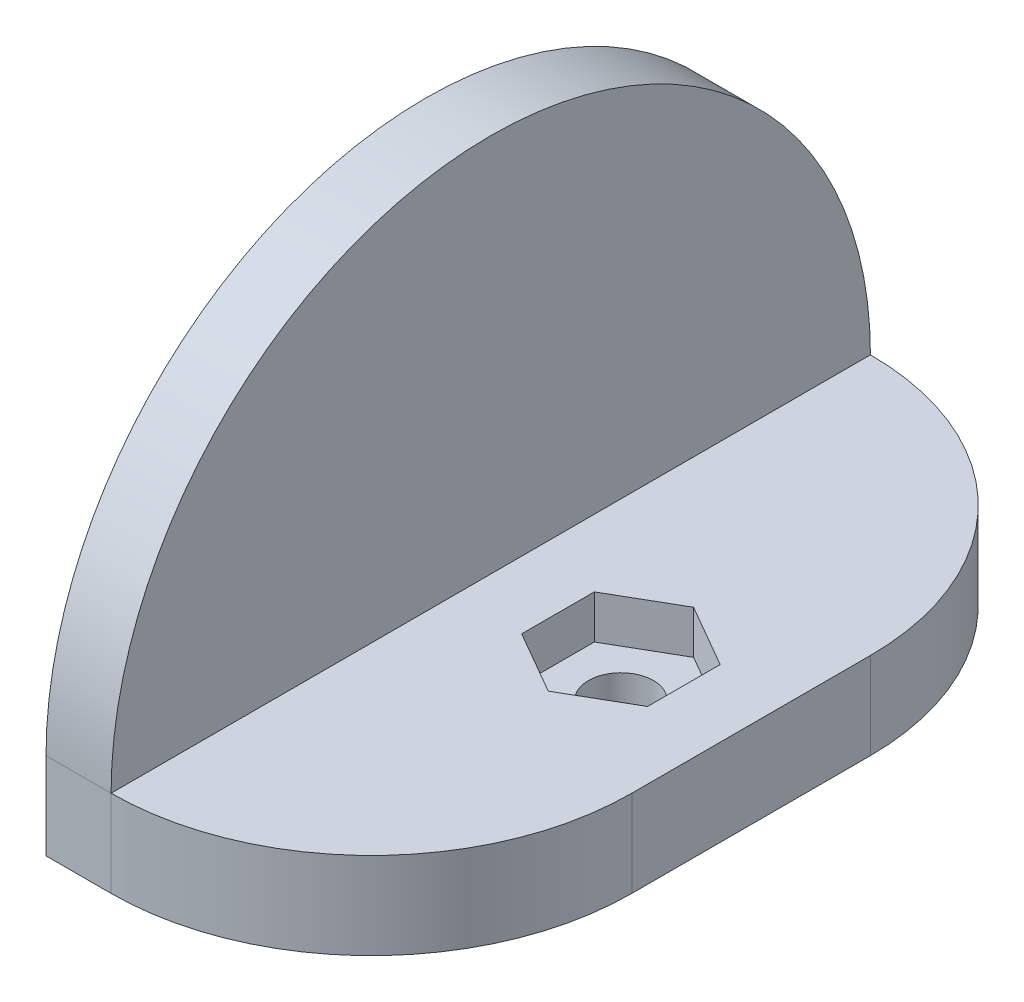
SolidWorks part; units mm, degrees
ref_plane "Alzado" through (0, 0, 0) normal (0, 0, 1) x (1, 0, 0)
ref_plane "Planta" through (0, 0, 0) normal (0, 1, 0) x (1, 0, 0)
ref_plane "Vista lateral" through (0, 0, 0) normal (1, 0, 0) x (0, 0, -1)
sketch "Croquis2" plane through (0, 0, 0) normal (0, 0, 1) x (1, 0, 0)
  line L0 (0, 23) -> (3, 23)
  line L1 (3, 23) -> (3, 4)
  line L2 (3, 4) -> (15, 4)
  line L3 (15, 4) -> (15, 0)
  line L4 (15, 0) -> (0, 0)
  line L5 (0, 0) -> (0, 23)
  dimension "D1" = 3
  dimension "D2" = 4
  dimension "D3" = 15
  dimension "D4" = 23
extrude "Saliente-Extruir1" add sketch "Croquis2" along normal blind 35
sketch "Croquis3" plane through (0, 4, 0) normal (0, 1, 0) x (1, 0, 0)
  line L0 (15, 0) -> (3, 0) construction
  line L1 (9, -14.1514) -> (6.1, -15.8257)
  line L2 (6.1, -15.8257) -> (6.1, -19.1743)
  line L3 (6.1, -19.1743) -> (9, -20.8486)
  line L4 (9, -20.8486) -> (11.9, -19.1743)
  line L5 (11.9, -19.1743) -> (11.9, -15.8257)
  line L6 (11.9, -15.8257) -> (9, -14.1514)
  line L7 (15, -35) -> (15, 0) construction
  circle A0 centre (9, -17.5) radius 2.9 construction
  dimension "D1" = 5.8
  dimension "D2" = 17.5
  dimension "D3" = 6
extrude "Cortar-Extruir1" cut sketch "Croquis3" against normal blind 2
sketch "Croquis4" plane through (0, 2, 0) normal (0, 1, 0) x (1, 0, 0)
  line L0 (6.1, -15.8257) -> (9, -17.5) construction
  line L1 (9, -17.5) -> (6.1, -19.1743) construction
  line L2 (6.1, -15.8257) -> (6.1, -19.1743) construction
  circle A0 centre (9, -17.5) radius 1.5
  dimension "D1" = 3
extrude "Cortar-Extruir2" cut sketch "Croquis4" against normal blind 10
sketch "Croquis5" plane through (0, 4, 0) normal (0, 1, 0) x (1, 0, 0)
  line L0 (3, -35) -> (3, 0) construction
  line L1 (15, -35) -> (15, 0) construction
  line L2 (15, -12) -> (15, -23)
  line L3 (3, -35) -> (3, -39.8617)
  line L4 (3, -39.8617) -> (21.6883, -36.8487)
  line L5 (21.6883, -36.8487) -> (27.2068, -6.8518)
  line L6 (27.2068, -6.8518) -> (15.8727, 7.7552)
  line L7 (15.8727, 7.7552) -> (3, 0)
  arc A0 (3, 0) -> (15, -12) centre (3, -12) cw
  arc A1 (3, -35) -> (15, -23) centre (3, -23) ccw
extrude "Cortar-Extruir3" cut sketch "Croquis5" against normal blind 10
sketch "Croquis6" plane through (3, 0, 0) normal (1, 0, 0) x (0, 0, -1)
  line L0 (-35, 4) -> (0, 4) construction
  line L3 (-35, 4) -> (-43.4632, 10.3059)
  line L4 (-43.4632, 10.3059) -> (-37.6486, 30.1853)
  line L5 (-37.6486, 30.1853) -> (-37.3311, 31.2707)
  line L6 (-37.3311, 31.2707) -> (8.7969, 26.4478)
  line L7 (8.7969, 26.4478) -> (6.3811, 12.0344)
  line L8 (6.3811, 12.0344) -> (0, 4)
  arc A0 (0, 4) -> (-35, 4) centre (-17.5, 4) ccw
extrude "Cortar-Extruir4" cut sketch "Croquis6" against normal blind 10
